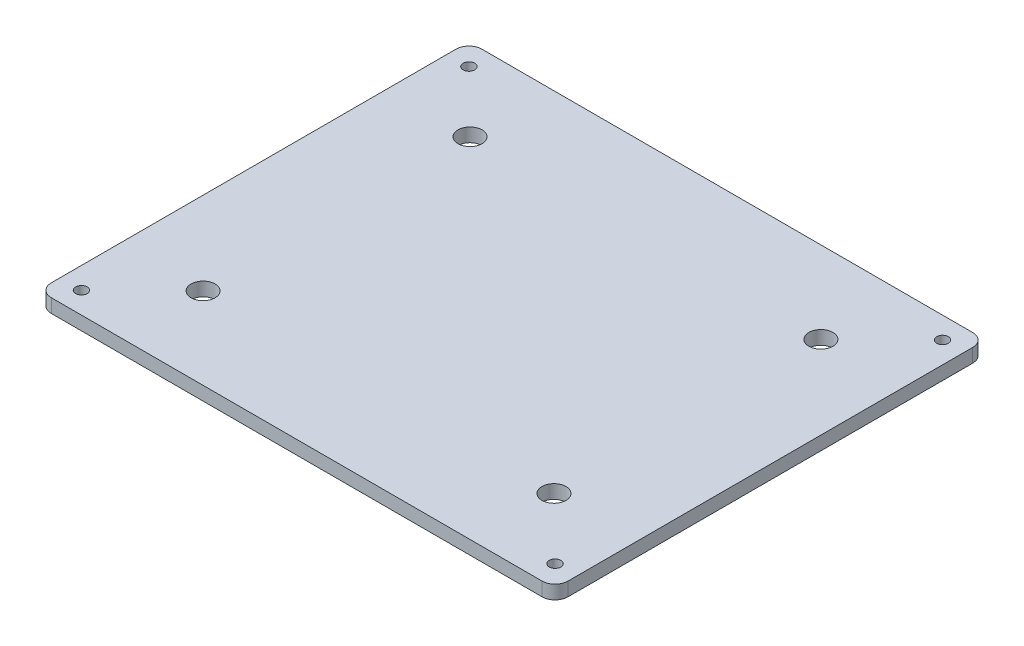
SolidWorks part; units mm, degrees
ref_plane "Front Plane" through (0, 0, 0) normal (0, 0, 1) x (1, 0, 0)
ref_plane "Top Plane" through (0, 0, 0) normal (0, 1, 0) x (1, 0, 0)
ref_plane "Right Plane" through (0, 0, 0) normal (1, 0, 0) x (0, 0, -1)
sketch "Sketch1" plane through (0, 0, 0) normal (0, 1, 0) x (1, 0, 0)
  line L1 (60, -50) -> (-60, -50)
  line L2 (60, -50) -> (60, 50)
  line L3 (60, 50) -> (-60, 50)
  line L4 (-60, -50) -> (-60, 50)
  line L5 (60, -50) -> (-60, 50) construction
  line L6 (60, 50) -> (-60, -50) construction
  line L8 (55, -45) -> (55, 45) construction
  point P0 (0, 0)
  point P6 (0, 0)
  dimension "D1" = 100
  dimension "D2" = 120
extrude "Boss-Extrude1" add sketch "Sketch1" along normal blind 3.175
sketch "Sketch2" plane through (0, 3.175, 0) normal (0, 1, 0) x (1, 0, 0)
  line L1 (55, -45) -> (-55, -45) construction
  line L2 (55, -45) -> (55, 45) construction
  line L3 (55, 45) -> (-55, 45) construction
  line L4 (-55, -45) -> (-55, 45) construction
  line L5 (55, -45) -> (-55, 45) construction
  line L6 (55, 45) -> (-55, -45) construction
  line L7 (40.75, -31) -> (-40.75, -31) construction
  line L8 (40.75, -31) -> (40.75, 31) construction
  line L9 (40.75, 31) -> (-40.75, 31) construction
  line L10 (-40.75, -31) -> (-40.75, 31) construction
  line L11 (40.75, -31) -> (-40.75, 31) construction
  line L12 (40.75, 31) -> (-40.75, -31) construction
  circle A0 centre (-40.75, 31) radius 2.794
  circle A1 centre (-40.75, -31) radius 2.794
  circle A2 centre (40.75, -31) radius 2.794
  circle A3 centre (40.75, 31) radius 2.794
  point P0 (0, 0)
  point P6 (0, 0)
  dimension "D5" = 5.588
  dimension "D1" = 90
  dimension "D2" = 110
  dimension "D3" = 62
  dimension "D4" = 81.5
extrude "Cut-Extrude1" cut sketch "Sketch2" against normal through all
hole_wizard "M2.5 Clearance Hole1" positions "Sketch3" profile "Sketch4" hole size "M2.5" standard "ANSI Metric" end condition through all
sketch "Sketch3" plane through (0, 3.175, 0) normal (0, 1, 0) x (1, 0, 0)
  point P0 (-55, 45)
  point P3 (55, 45)
  point P6 (-55, -45)
  point P9 (55, -45)
sketch "Sketch4" plane through (-55, 3.175, -45) normal (1, 0, 0) x (0, 0, 1)
  line L0 (0, 0) -> (0, 3.175)
  line L1 (0, 3.175) -> (1.35, 3.175)
  line L2 (1.35, 3.175) -> (1.35, 0)
  line L5 (1.35, 0) -> (0, 0)
  line L11 (0, -6.35) -> (0, 107.95) construction
  dimension "Thru Hole Dia." = 2.7
  dimension "Thru Hole Depth" = 3.175
fillet "Fillet1" radius 3 4 edges at (60, 1.5875, -50) (60, 1.5875, 50) (-60, 1.5875, 50) (-60, 1.5875, -50)
